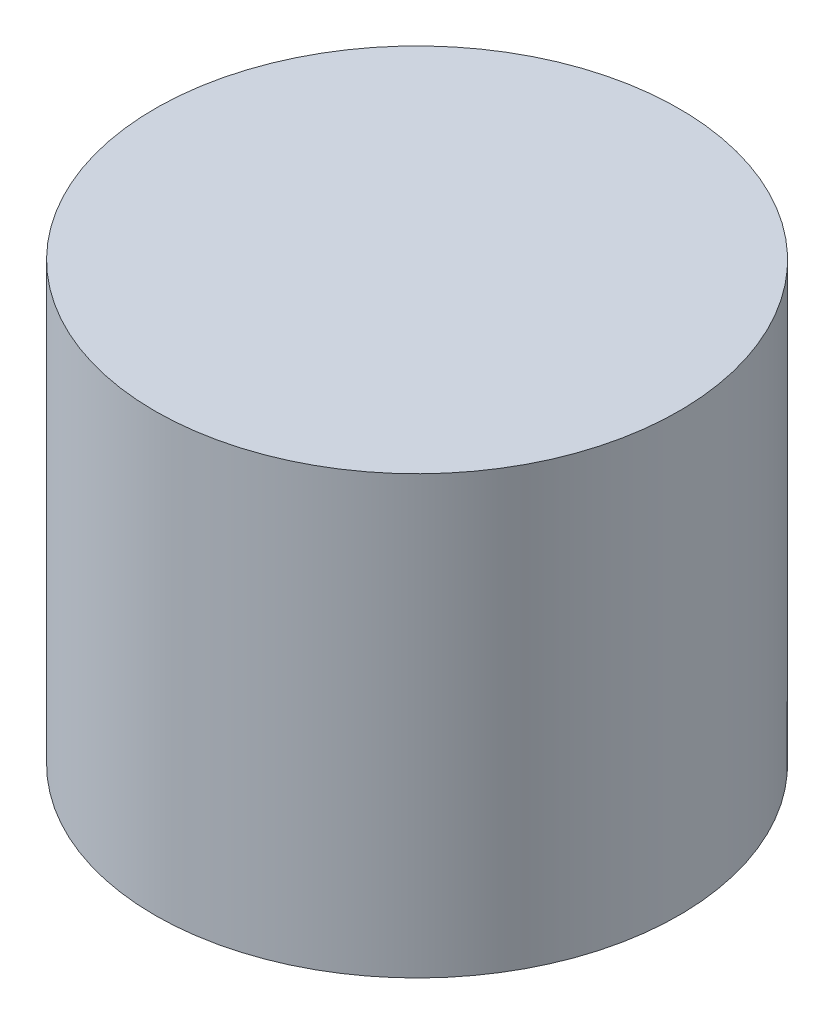
SolidWorks part; units mm, degrees
ref_plane "Front Plane" through (0, 0, 0) normal (0, 0, 1) x (1, 0, 0)
ref_plane "Top Plane" through (0, 0, 0) normal (0, 1, 0) x (1, 0, 0)
ref_plane "Right Plane" through (0, 0, 0) normal (1, 0, 0) x (0, 0, -1)
sketch "Sketch1" plane through (0, 0, 0) normal (0, 1, 0) x (1, 0, 0)
  circle A0 centre (0, 0) radius 3
extrude "Boss-Extrude1" add sketch "Sketch1" along normal blind 5
